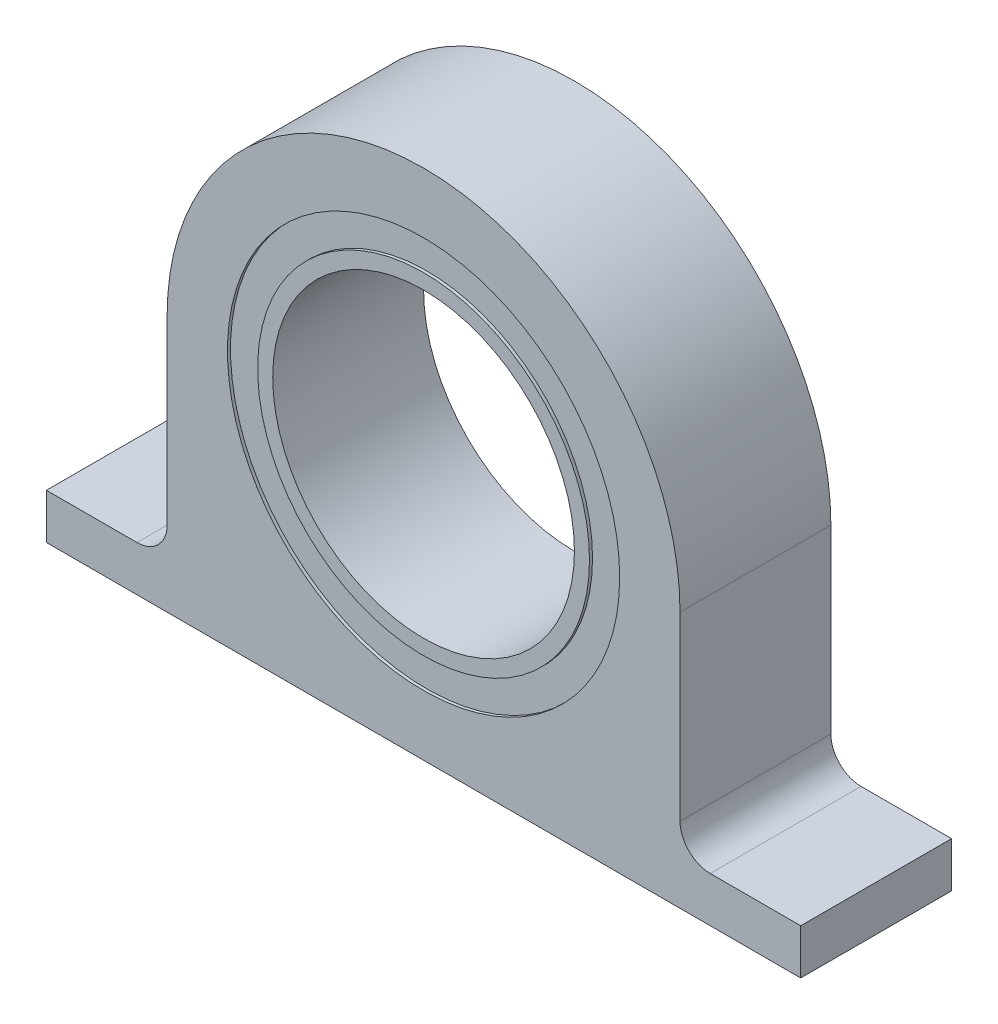
SolidWorks part; units mm, degrees
ref_plane "Front Plane" through (0, 0, 0) normal (0, 0, 1) x (1, 0, 0)
ref_plane "Top Plane" through (0, 0, 0) normal (0, 1, 0) x (1, 0, 0)
ref_plane "Right Plane" through (0, 0, 0) normal (1, 0, 0) x (0, 0, -1)
sketch "Sketch1" plane through (0, 0, 0) normal (0, 0, 1) x (1, 0, 0)
  circle A2 centre (0, 0) radius 12.7
  circle A3 centre (0, 0) radius 17.78
  dimension "D1" = 25.4
  dimension "D2" = 35.56
extrude "Boss-Extrude1" add sketch "Sketch1" along normal blind 12.7
sketch "Sketch2" plane through (0, 0, 12.7) normal (0, 0, 1) x (1, 0, 0)
  circle A0 centre (0, 0) radius 12.7 construction
  circle A1 centre (0, 0) radius 12.7
  circle A2 centre (0, 0) radius 16.51
  circle A3 centre (0, 0) radius 13.97
  dimension "D1" = 33.02
  dimension "D2" = 27.94
extrude "Cut-Extrude1" cut sketch "Sketch2" against normal blind 0.254 contours A2 A3
ref_plane "Plane1" through (0, 0, 6.35) normal (0, 0, 1) x (1, 0, 0)
mirror "Mirror1" about plane through (0, 0, 6.35) normal (0, 0, 1) of "Cut-Extrude1"
sketch "Sketch3" plane through (0, 0, 0) normal (0, 0, 1) x (1, 0, 0)
  line L0 (0, 17.78) -> (0, -17.78) construction
  line L1 (-31.75, -17.78) -> (31.75, -17.78) construction
  line L2 (-31.75, -21.59) -> (31.75, -21.59)
  line L3 (-21.59, -17.78) -> (-21.59, 0) construction
  line L4 (21.59, -17.78) -> (21.59, 0) construction
  line L5 (-31.75, -17.78) -> (-24.13, -17.78)
  line L6 (-31.75, -17.78) -> (-31.75, -21.59)
  line L7 (31.75, -17.78) -> (31.75, -21.59)
  line L8 (-21.59, 0) -> (-21.59, -15.24)
  line L10 (21.59, -15.24) -> (21.59, 0)
  line L11 (24.13, -17.78) -> (31.75, -17.78)
  circle A0 centre (0, 0) radius 17.78 construction
  arc A1 (-21.59, 0) -> (21.59, 0) centre (0, 0) cw
  arc A2 (-24.13, -17.78) -> (-21.59, -15.24) centre (-24.13, -15.24) ccw
  arc A3 (21.59, -15.24) -> (24.13, -17.78) centre (24.13, -15.24) ccw
  circle A5 centre (0, 0) radius 17.78
  point P7 (0, -17.78)
  dimension "D4" = 2.54
  dimension "D1" = 63.5
  dimension "D2" = 3.81
  dimension "D3" = 21.59
extrude "Boss-Extrude3" add sketch "Sketch3" along normal up to surface (12.7 mm away) contours L5 A2 L8 A1 L10 A3 L11 L7 L2 L6
equation "\"Shaftdia\"=1"
equation "\"D1@Sketch1\"=\"Shaftdia\""
equation "\"D2@Sketch1\"=\"Shaftdia\"+0.4in"
equation "\"D1@Sketch2\"=\"Shaftdia\"+0.3in"
equation "\"D2@Sketch2\"=\"Shaftdia\"+0.1"
